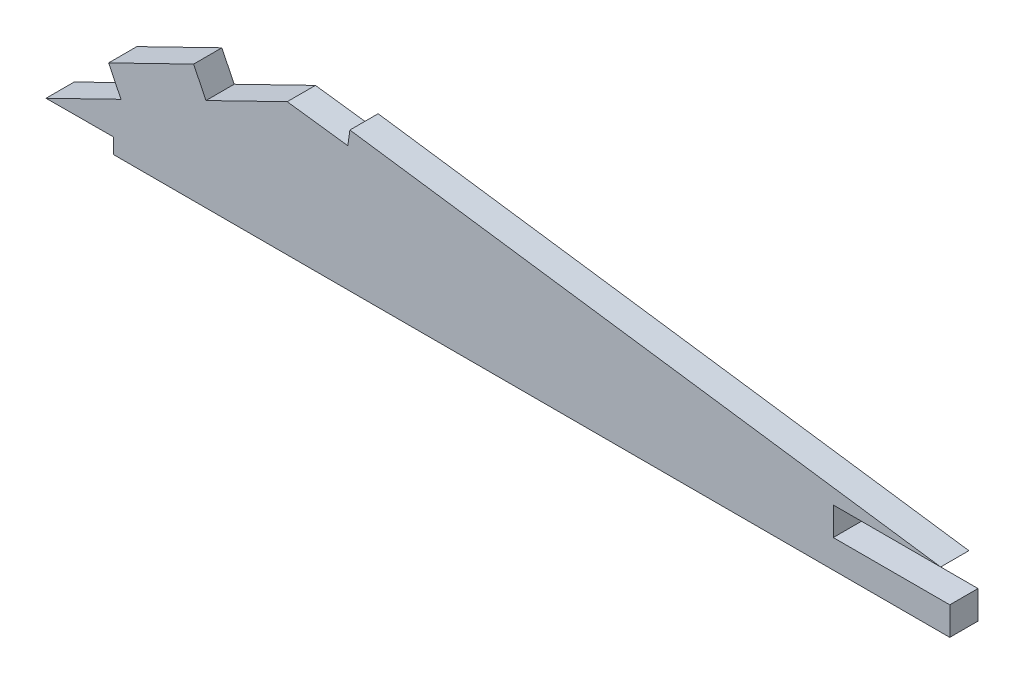
SolidWorks part; units mm, degrees
ref_plane "前视基准面" through (0, 0, 0) normal (0, 0, 1) x (1, 0, 0)
ref_plane "上视基准面" through (0, 0, 0) normal (0, 1, 0) x (1, 0, 0)
ref_plane "右视基准面" through (0, 0, 0) normal (1, 0, 0) x (0, 0, -1)
sketch "Model" plane through (0, 0, 0) normal (0, 0, 1) x (1, 0, 0)
  line L0 (2.0887, 3.9101) -> (7.4032, 6.5022)
  line L1 (6.5265, 8.2998) -> (12.5489, 11.2371)
  line L2 (12.5489, 11.2371) -> (13.4256, 9.4395)
  line L3 (6.5265, 8.2998) -> (7.4032, 6.5022)
  line L4 (13.4256, 9.4395) -> (19.1819, 12.247)
  line L5 (6.8743, 2.8455) -> (66.1354, 2.8455)
  line L6 (6.8743, 2.8455) -> (6.8701, 3.9287)
  line L7 (6.8701, 3.9287) -> (2.0887, 3.9101)
  line L8 (57.8793, 4.8455) -> (66.1354, 4.8455)
  line L9 (57.8793, 6.8455) -> (65.4894, 6.8455)
  line L10 (57.8793, 4.8455) -> (57.8793, 6.8455)
  line L11 (66.1354, 2.8455) -> (66.1354, 4.8455)
  line L12 (23.6243, 12.7293) -> (65.4894, 6.8455)
  line L13 (19.1819, 12.247) -> (23.4761, 11.6916)
  line L14 (23.4761, 11.6916) -> (23.6243, 12.7293)
  point P16 (0, 0)
extrude "凸台-拉伸1" add sketch "Model" along normal blind 2
